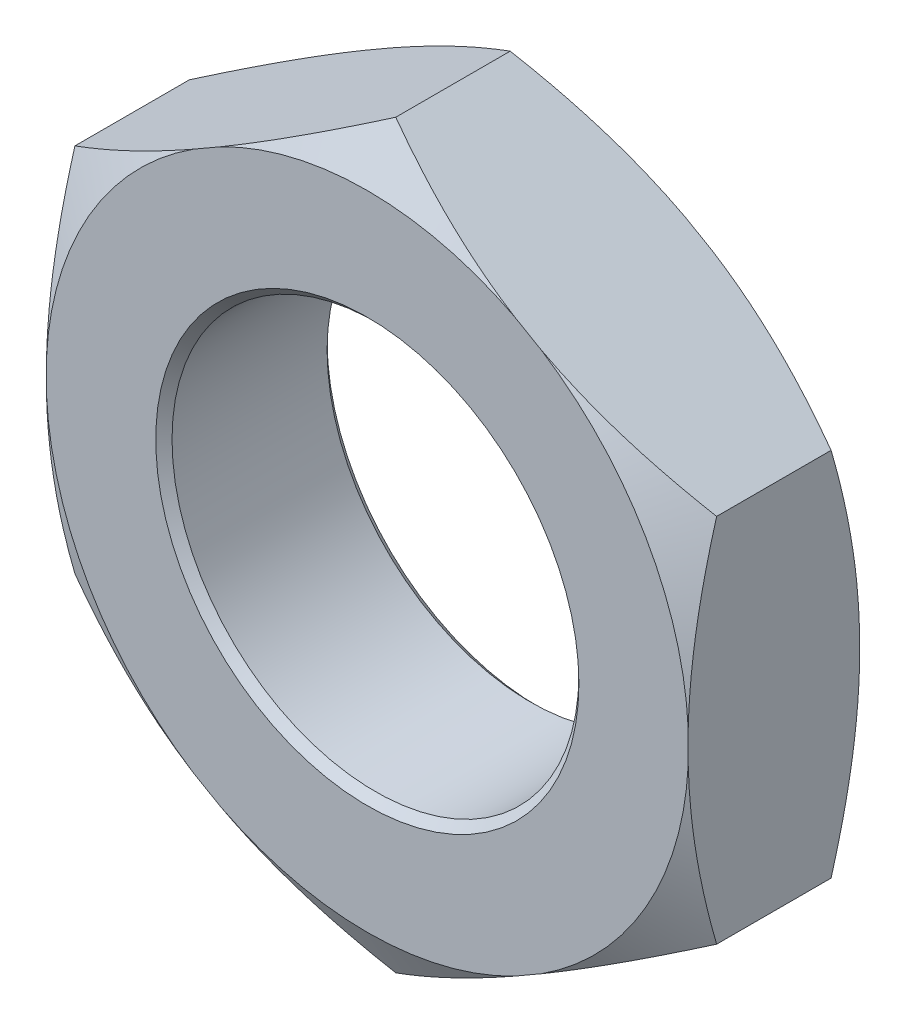
SolidWorks part; units mm, degrees
ref_plane "Front" through (0, 0, 0) normal (0, 0, 1) x (1, 0, 0)
ref_plane "Top" through (0, 0, 0) normal (0, 1, 0) x (1, 0, 0)
ref_plane "Right" through (0, 0, 0) normal (1, 0, 0) x (0, 0, -1)
sketch "Sketch2" plane through (0, 0, 0) normal (1, 0, 0) x (0, 0, -1)
  line L0 (0, 0) -> (0, -17.1157) construction
  line L1 (-4, 9.5) -> (-4, 15)
  line L2 (-4, 15) -> (-2.6721, 17.3)
  line L3 (-2.6721, 17.3) -> (2.6721, 17.3)
  line L4 (4, 15) -> (2.6721, 17.3)
  line L5 (4, 9.5) -> (4, 15)
  line L7 (-4, 9.5) -> (4, 9.5)
  line L8 (-27.3892, 0) -> (-39.7755, 0) construction
  point P8 (0, 17.3)
  dimension "D1" = 60
  dimension "H" = 8
  dimension "D3" = 19
  dimension "C" = 34.6
  dimension "B" = 30
revolve "Body" add sketch "Sketch2" angle 360 about L8
sketch "Sketch3" plane through (0, 0, 4) normal (0, 0, 1) x (1, 0, 0)
  line L1 (14.9822, -8.65) -> (14.9822, 8.65)
  line L2 (14.9822, 8.65) -> (0, 17.3)
  line L3 (0, 17.3) -> (-14.9822, 8.65)
  line L4 (-14.9822, 8.65) -> (-14.9822, -8.65)
  line L5 (-14.9822, -8.65) -> (0, -17.3)
  line L6 (0, -17.3) -> (14.9822, -8.65)
  circle A0 centre (0, 0) radius 14.9822 construction
  circle A2 centre (0, 0) radius 17.3 construction
extrude "Hex" cut sketch "Sketch3" against normal through all flip side to cut
chamfer "InnerChamfer" distance 0.38 angle 45 2 edges at (-9.5, 0, -4) (-9.5, 0, 4)
sketch "Sketch4" [suppressed] plane through (0, 0, 5) normal (0, 0, 1) x (1, 0, 0)
  circle A0 centre (0, 0) radius 22.5
  dimension "D1" = 45
extrude "TrunnionNutEdgeCut" [suppressed] cut sketch "Sketch4" against normal blind 10 flip side to cut
